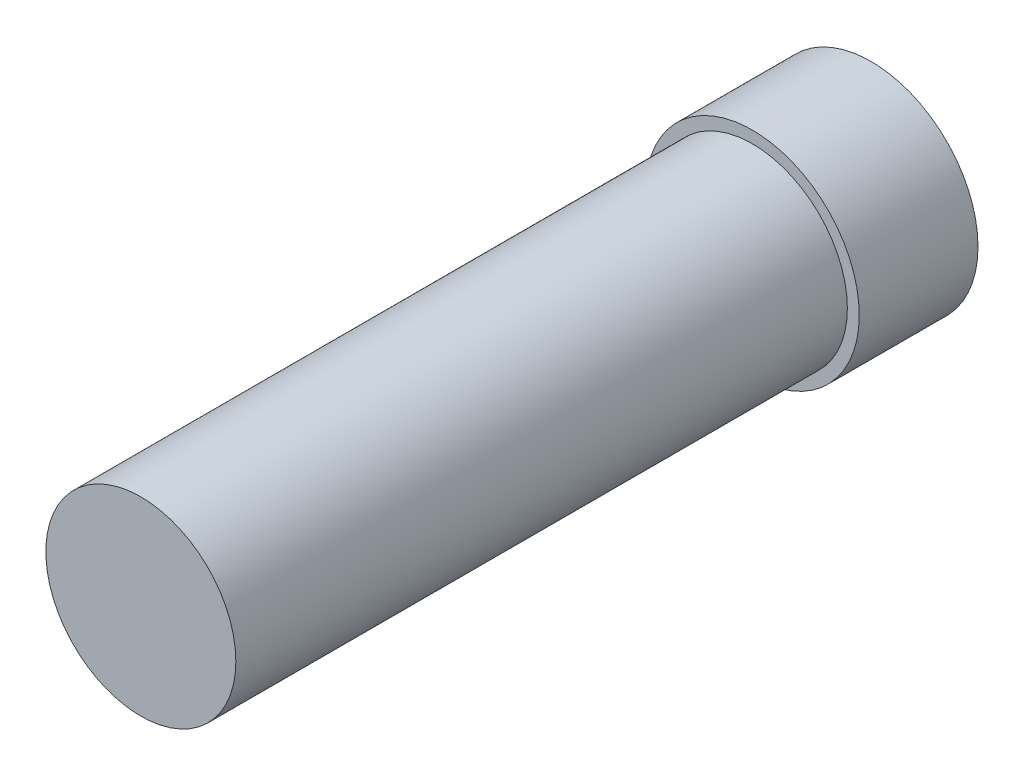
SolidWorks part; units mm, degrees
material "Brass"
ref_plane "Front Plane" through (0, 0, 0) normal (0, 0, 1) x (1, 0, 0)
ref_plane "Top Plane" through (0, 0, 0) normal (0, 1, 0) x (1, 0, 0)
ref_plane "Right Plane" through (0, 0, 0) normal (1, 0, 0) x (0, 0, -1)
sketch "Sketch1" plane through (0, 0, 0) normal (0, 0, 1) x (1, 0, 0)
  circle A0 centre (0, 0) radius 2.032
extrude "Boss-Extrude1" add sketch "Sketch1" along normal blind 13.08
sketch "Sketch2" plane through (0, 0, 0) normal (0, 0, -1) x (-1, 0, 0)
  circle A0 centre (0, 0) radius 2.286
  dimension "D1" = 4.572
extrude "Boss-Extrude2" add sketch "Sketch2" along normal blind 2.54
sketch "Sketch3" plane through (0, 0, -2.54) normal (0, 0, -1) x (-1, 0, 0)
  line L1 (0, -1.5547) -> (1.3464, -0.7774)
  line L2 (1.3464, -0.7774) -> (1.3464, 0.7774)
  line L3 (1.3464, 0.7774) -> (0, 1.5547)
  line L4 (0, 1.5547) -> (-1.3464, 0.7774)
  line L5 (-1.3464, 0.7774) -> (-1.3464, -0.7774)
  line L6 (-1.3464, -0.7774) -> (0, -1.5547)
  circle A0 centre (0, 0) radius 1.3464 construction
extrude "Cut-Extrude1" cut sketch "Sketch3" against normal blind 2.032
